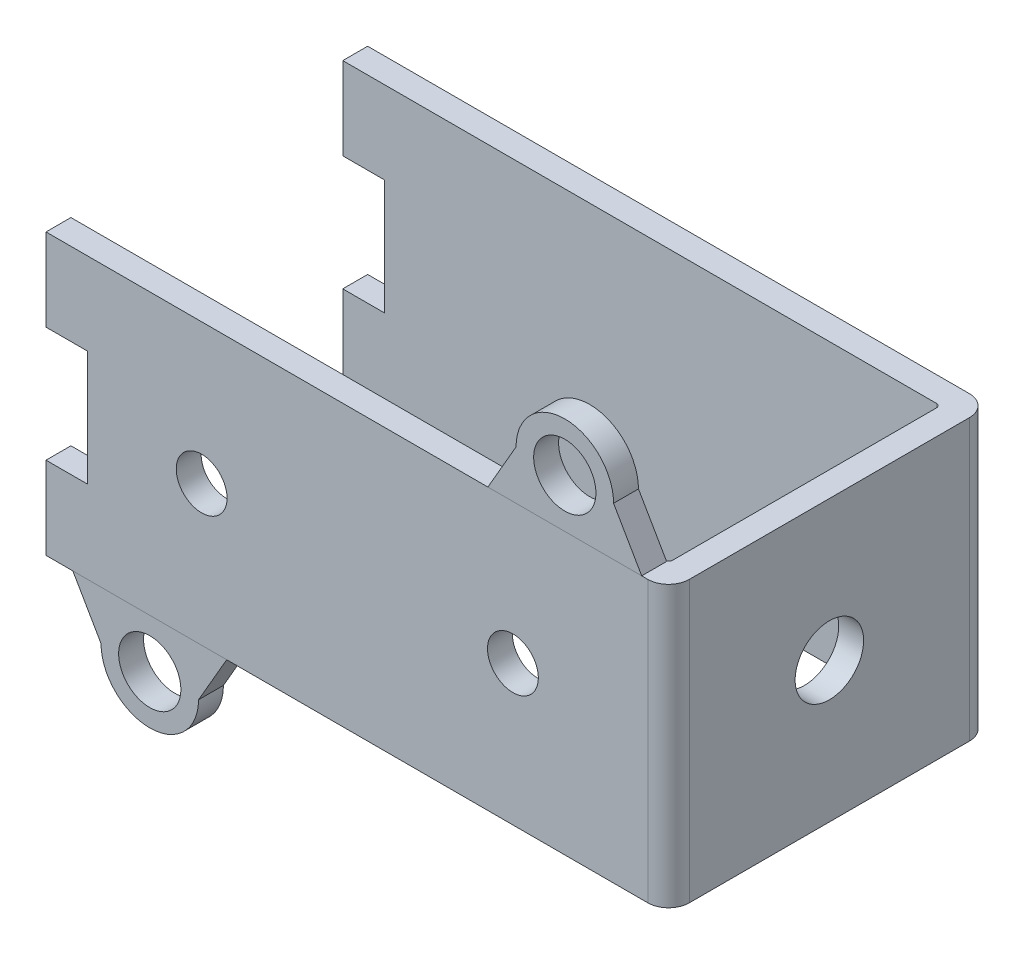
SolidWorks part; units mm, degrees
ref_plane "Alzado" through (0, 0, 0) normal (0, 0, 1) x (1, 0, 0)
ref_plane "Planta" through (0, 0, 0) normal (0, 1, 0) x (1, 0, 0)
ref_plane "Vista lateral" through (0, 0, 0) normal (1, 0, 0) x (0, 0, -1)
sketch "Croquis1" plane through (0, 0, 0) normal (0, 1, 0) x (1, 0, 0)
  line L0 (-15, 7.75) -> (15, -7.75) construction
  line L1 (-15, 7.75) -> (15, 7.75)
  line L2 (-15, 7.75) -> (-15, -7.75)
  line L3 (-15, -7.75) -> (15, -7.75)
  line L4 (15, 7.75) -> (15, -7.75)
  point P4 (0, 0)
  dimension "D1" = 15.5
  dimension "D2" = 30
extrude "Saliente-Extruir1" add sketch "Croquis1" along normal mid plane 13.5
sketch "Croquis2" plane through (0, 0, 0) normal (0, 1, 0) x (1, 0, 0)
  line L0 (-15, 7.75) -> (-15, -7.75) construction
  line L1 (-15, -6.55) -> (13.8, -6.55)
  line L2 (-15, -6.55) -> (-15, 6.55)
  line L3 (-15, 6.55) -> (13.8, 6.55)
  line L4 (13.8, -6.55) -> (13.8, 6.55)
  line L5 (15, 7.75) -> (-15, 7.75) construction
  line L6 (15, -7.75) -> (15, 7.75) construction
  point P6 (-15, 0)
  point P7 (-15, 0)
  dimension "D1" = 1.2
  dimension "D2" = 1.2
extrude "Cortar-Extruir1" cut sketch "Croquis2" against normal through all both and the other way through all
sketch "Croquis3" plane through (15, 0, 0) normal (1, 0, 0) x (0, 0, -1)
  circle A0 centre (0, 0) radius 1.65
  dimension "D1" = 3.3
extrude "Cortar-Extruir2" cut sketch "Croquis3" against normal up to next
fillet "Redondeo1" radius 1 2 edges at (15, 0, 7.75) (15, 0, -7.75)
fillet "Redondeo2" radius 0.2 2 edges at (13.8, 0, 6.55) (13.8, 0, -6.55)
sketch "Croquis4" plane through (0, 0, 0) normal (0, 0, 1) x (1, 0, 0)
  line L0 (-15, 6.75) -> (-15, -6.75) construction
  line L1 (-15, 2.775) -> (-13, 2.775)
  line L2 (-15, 2.775) -> (-15, -2.775)
  line L3 (-15, -2.775) -> (-13, -2.775)
  line L4 (-13, 2.775) -> (-13, -2.775)
  point P4 (-15, 0)
  point P7 (-15, 0)
  dimension "D1" = 5.55
  dimension "D2" = 2
extrude "Cortar-Extruir3" cut sketch "Croquis4" against normal through all both and the other way through all
sketch "Croquis5" plane through (0, 0, 7.75) normal (0, 0, 1) x (1, 0, 0)
  line L0 (15, 6.75) -> (15, -6.75) construction
  circle A0 centre (-7.5, 0) radius 1.225
  circle A1 centre (7.5, 0) radius 1.225
  dimension "D1" = 2.45
  dimension "D2" = 15
  dimension "D3" = 7.5
extrude "Cortar-Extruir4" cut sketch "Croquis5" against normal up to next
sketch "Sketch1" plane through (0, 0, 7.75) normal (0, 0, 1) x (1, 0, 0)
  line L0 (-15, 6.75) -> (14, 6.75) construction
  line L1 (-15, -6.75) -> (14, -6.75) construction
  line L2 (-15, -2.775) -> (-15, -6.75) construction
  line L3 (12.35, 9.1) -> (13.7068, 6.75)
  line L4 (10, 9.1) -> (10, 15.9635) construction
  line L5 (7.65, 9.1) -> (6.2932, 6.75)
  line L6 (-12.35, -9.1) -> (-13.7068, -6.75)
  line L7 (-10, -9.1) -> (-10, -15.4046) construction
  line L8 (-7.65, -9.1) -> (-6.2932, -6.75)
  line L9 (13.7068, 6.75) -> (6.2932, 6.75)
  line L10 (-6.2932, -6.75) -> (-13.7068, -6.75)
  circle A0 centre (10, 9.1) radius 2.35
  circle A1 centre (-10, -9.1) radius 2.35
  circle A2 centre (-10, -9.1) radius 1.5
  circle A3 centre (10, 9.1) radius 1.5
  line M8 (-15, -6.75) -> (14, -6.75)
  line M10 (14, 6.75) -> (-15, 6.75)
  dimension "D6" = 3
  dimension "D7" = 3
  dimension "D1" = 18.2
  dimension "D2" = 20
  dimension "D3" = 5
  dimension "D4" = 60
  dimension "D5" = 60
extrude "Boss-Extrude2" add sketch "Sketch1" against normal up to surface (1.2 mm away) separate body contours A0 A3 | A0 L3 M10 | A0 L5 L9 | A1 L8 L10 | A1 A2 | A1 L6 M8 up to face at (8.725, 0, 6.55)
